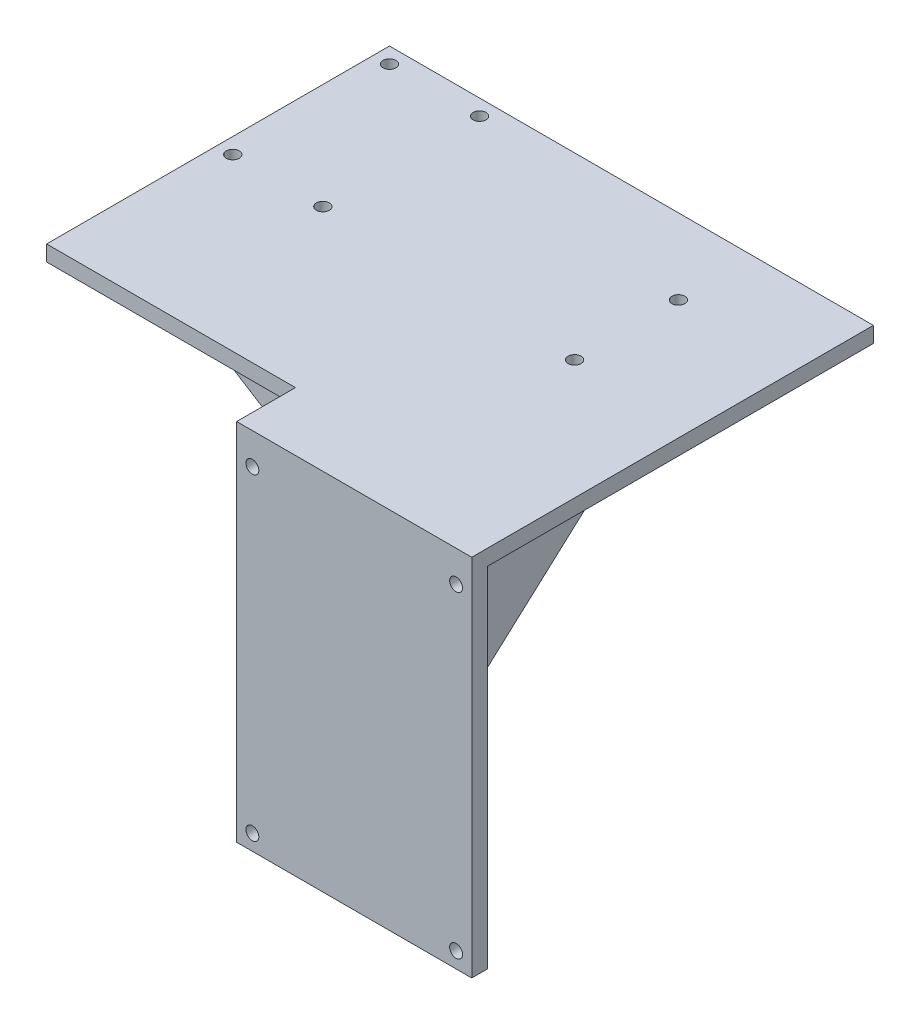
SolidWorks part; units mm, degrees
ref_plane "Front Plane" through (0, 0, 0) normal (0, 0, 1) x (1, 0, 0)
ref_plane "Top Plane" through (0, 0, 0) normal (0, 1, 0) x (1, 0, 0)
ref_plane "Right Plane" through (0, 0, 0) normal (1, 0, 0) x (0, 0, -1)
sketch "Sketch1" plane through (0, 0, 0) normal (0, 0, 1) x (1, 0, 0)
  line L1 (0, 0) -> (60, 0)
  line L2 (0, 0) -> (0, -93)
  line L3 (0, -93) -> (60, -93)
  line L4 (60, 0) -> (60, -93)
  dimension "D1" = 93
  dimension "D2" = 60
extrude "Boss-Extrude1" add sketch "Sketch1" against normal blind 4
sketch "Sketch2" plane through (0, 0, 0) normal (0, 0, 1) x (1, 0, 0)
  line L0 (0, 0) -> (0, -93) construction
  line L1 (60, 0) -> (0, 0)
  line L2 (60, 0) -> (60, -4)
  line L3 (60, -4) -> (0, -4)
  line L4 (0, 0) -> (0, -4)
  dimension "D1" = 4
sketch "Sketch3" plane through (0, 0, 0) normal (0, 0, 1) x (1, 0, 0)
  line L0 (60, -4) -> (0, -4) construction
  line L1 (0, 0) -> (0, -93) construction
  line L2 (60, -93) -> (60, 0) construction
  line L3 (0, -93) -> (60, -93) construction
  circle A0 centre (4, -8) radius 1.65
  circle A1 centre (56, -8) radius 1.65
  circle A2 centre (4, -89) radius 1.65
  circle A3 centre (56, -89) radius 1.65
  dimension "D1" = 3.3
  dimension "D4" = 3.3
  dimension "D9" = 3.3
  dimension "D12" = 3.3
  dimension "D2" = 4
  dimension "D3" = 4
  dimension "D5" = 4
  dimension "D6" = 4
  dimension "D7" = 4
  dimension "D8" = 4
  dimension "D10" = 4
  dimension "D11" = 4
extrude "Cut-Extrude1" cut sketch "Sketch3" against normal blind 4
sketch "Sketch5" plane through (0, 0, -4) normal (0, 0, -1) x (-1, 0, 0)
  line L0 (0, 0) -> (0, -93) construction
  line L1 (-60, 0) -> (0, 0)
  line L2 (-60, 0) -> (-60, -4)
  line L3 (-60, -4) -> (0, -4)
  line L4 (0, 0) -> (0, -4)
  dimension "D1" = 4
extrude "Boss-Extrude2" add sketch "Sketch5" along normal blind 11
sketch "Sketch6" plane through (0, 0, -15) normal (0, 0, -1) x (-1, 0, 0)
  line L1 (-60, -4) -> (63.5, -4)
  line L2 (-60, -4) -> (-60, 0)
  line L3 (-60, 0) -> (63.5, 0)
  line L4 (63.5, -4) -> (63.5, 0)
  dimension "D1" = 123.5
  dimension "D2" = 4
extrude "Boss-Extrude3" add sketch "Sketch6" along normal blind 87.5
sketch "Sketch7" plane through (0, 0, 0) normal (0, 1, 0) x (1, 0, 0)
  line L0 (-63.5, 102.5) -> (60, 102.5) construction
  line L1 (-63.5, 102.5) -> (-63.5, 15) construction
  circle A0 centre (-59.5, 98.5) radius 1.65
  circle A1 centre (-36.5, 98.5) radius 1.65
  circle A2 centre (-59.5, 58.5) radius 1.65
  circle A3 centre (-36.5, 58.5) radius 1.65
  dimension "D5" = 3.3
  dimension "D6" = 3.3
  dimension "D9" = 3.3
  dimension "D11" = 44
  dimension "D12" = 3.3
  dimension "D1" = 4
  dimension "D2" = 4
  dimension "D3" = 4
  dimension "D4" = 23
  dimension "D7" = 4
  dimension "D8" = 40
  dimension "D10" = 23
extrude "Cut-Extrude2" cut sketch "Sketch7" against normal blind 87.5
sketch "Sketch8" plane through (0, 0, 0) normal (0, 1, 0) x (1, 0, 0)
  line L1 (-36.5, 58.5) -> (-18, 58.5)
  line L2 (-36.5, 58.5) -> (-36.5, 70)
  line L3 (-36.5, 70) -> (-18, 70)
  line L4 (-18, 58.5) -> (-18, 70)
  dimension "D1" = 18.5
  dimension "D2" = 11.5
sketch "Sketch9" plane through (0, 0, 0) normal (0, 1, 0) x (1, 0, 0)
  line L1 (-18, 70) -> (29.5, 70)
  line L2 (-18, 70) -> (-18, 83.25)
  line L3 (-18, 83.25) -> (29.5, 83.25)
  line L4 (29.5, 70) -> (29.5, 83.25)
  line L5 (-18, 70) -> (29.5, 70)
  line L6 (-18, 70) -> (-18, 56.75)
  line L7 (-18, 56.75) -> (29.5, 56.75)
  line L8 (29.5, 70) -> (29.5, 56.75)
  dimension "D1" = 13.25
  dimension "D2" = 47.5
  dimension "D3" = 13.25
sketch "Sketch10" plane through (0, 0, 0) normal (0, 1, 0) x (1, 0, 0)
  circle A0 centre (29.5, 83.25) radius 1.65
  circle A1 centre (29.5, 56.75) radius 1.65
  dimension "D1" = 3.3
  dimension "D2" = 3.3
extrude "Cut-Extrude3" cut sketch "Sketch10" against normal blind 10
sketch "Sketch11" plane through (0, 0, 0) normal (1, 0, 0) x (0, 0, -1)
  line L0 (15, -4) -> (4, -4) construction
  line L1 (4, -93) -> (102.5, -93)
  line L2 (4, -93) -> (4, -4)
  line L3 (4, -4) -> (102.5, -4)
  line L4 (102.5, -93) -> (102.5, -4)
  line L5 (4, -4) -> (4, -93) construction
  dimension "D1" = 0
  dimension "D2" = 89
  dimension "D3" = 98.5
  dimension "D4" = 0
extrude "Boss-Extrude4" add sketch "Sketch11" along normal blind 25
sketch "Sketch13" plane through (0, 0, 0) normal (-1, 0, 0) x (0, 0, 1)
  line L0 (-102.5, -93) -> (0, -93) construction
  line L1 (-102.5, -4) -> (-4, -4)
  line L2 (-102.5, -4) -> (-102.5, -93)
  line L3 (-102.5, -93) -> (-4, -93)
  line L4 (-4, -4) -> (-4, -93)
  line L5 (0, 0) -> (0, -93) construction
  dimension "D1" = 4
extrude "Cut-Extrude5" cut sketch "Sketch13" against normal blind 8
sketch "Sketch14" plane through (8, 0, 0) normal (-1, 0, 0) x (0, 0, 1)
  line L0 (-102.5, -4) -> (-102.5, -93)
  line L1 (-102.5, -93) -> (-4, -93)
  line L2 (-102.5, -4) -> (-4, -93)
extrude "Cut-Extrude7" cut sketch "Sketch14" against normal blind 20
sketch "Sketch15" plane through (0, -4, 0) normal (0, -1, 0) x (1, 0, 0)
  line L0 (-63.5, -102.5) -> (-63.5, -15) construction
  line L1 (-63.5, -50.5) -> (8, -50.5)
  line L2 (-63.5, -50.5) -> (-63.5, -33.5)
  line L3 (-63.5, -33.5) -> (8, -33.5)
  line L4 (8, -50.5) -> (8, -33.5)
  line L5 (8, -4) -> (8, -102.5) construction
  line L6 (0, -15) -> (-63.5, -15) construction
  circle A0 centre (-59.5, -58.5) radius 1.65 construction
  dimension "D1" = 8
  dimension "D2" = 18.5
  dimension "D3" = 17
extrude "Boss-Extrude6" add sketch "Sketch15" along normal blind 45
sketch "Sketch16" plane through (0, 0, -50.5) normal (0, 0, -1) x (-1, 0, 0)
  line L0 (63.5, -4) -> (-8, -49)
  line L1 (63.5, -49) -> (63.5, -4)
  line L2 (-8, -49) -> (63.5, -49)
extrude "Cut-Extrude9" cut sketch "Sketch16" against normal blind 45
